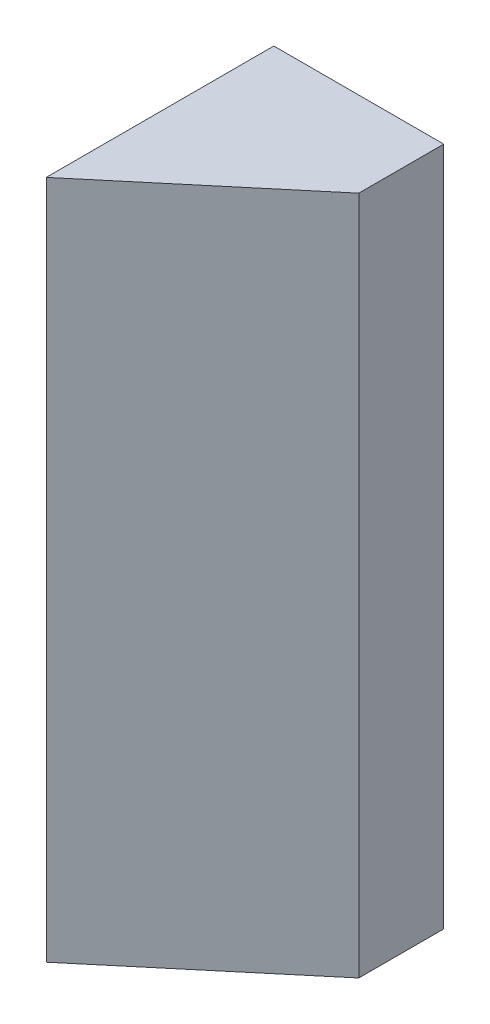
SolidWorks part; units mm, degrees
ref_plane "Front Plane" through (0, 0, 0) normal (0, 0, 1) x (1, 0, 0)
ref_plane "Top Plane" through (0, 0, 0) normal (0, 1, 0) x (1, 0, 0)
ref_plane "Right Plane" through (0, 0, 0) normal (1, 0, 0) x (0, 0, -1)
sketch "Sketch1" plane through (0, 0, 0) normal (0, 0, 1) x (1, 0, 0)
  line L1 (-3.175, 12.7) -> (3.175, 12.7)
  line L2 (-3.175, 12.7) -> (-3.175, -12.7)
  line L3 (-3.175, -12.7) -> (3.175, -12.7)
  line L4 (3.175, 12.7) -> (3.175, -12.7)
  line L5 (-3.175, 12.7) -> (3.175, -12.7) construction
  line L6 (-3.175, -12.7) -> (3.175, 12.7) construction
  point P0 (0, 0)
  dimension "D1" = 25.4
  dimension "D2" = 6.35
extrude "Boss-Extrude1" add sketch "Sketch1" along normal blind 3.175
sketch "Sketch2" plane through (0, 12.7, 0) normal (0, 1, 0) x (1, 0, 0)
  line L0 (-3.175, -3.175) -> (-3.175, -8.5033)
  line L1 (-3.175, -8.5033) -> (3.175, -3.175)
  line L2 (3.175, -3.175) -> (-3.175, -3.175)
  dimension "D1" = 40
extrude "Boss-Extrude2" add sketch "Sketch2" against normal up to surface (25.4 mm away) up to face at (0, -12.7, 1.5875)
sketch "Sketch3" plane through (0, 0, 0) normal (0, 0, -1) x (-1, 0, 0)
  line L0 (0, 12.7) -> (0, -12.7) construction
  line L1 (-3.175, 12.7) -> (3.175, 12.7) construction
  line L2 (3.175, -12.7) -> (-3.175, -12.7) construction
  circle A0 centre (0, 4.2333) radius 1.5875
  circle A1 centre (0, -4.2333) radius 1.5875
  point P10 (0, -6.1239)
  dimension "D1" = 3.175
  dimension "D2" = 3.175
  dimension "D3" = 8.4667
  dimension "D4" = 16.9333
extrude "Cut-Extrude1" cut sketch "Sketch3" against normal blind 3.175
